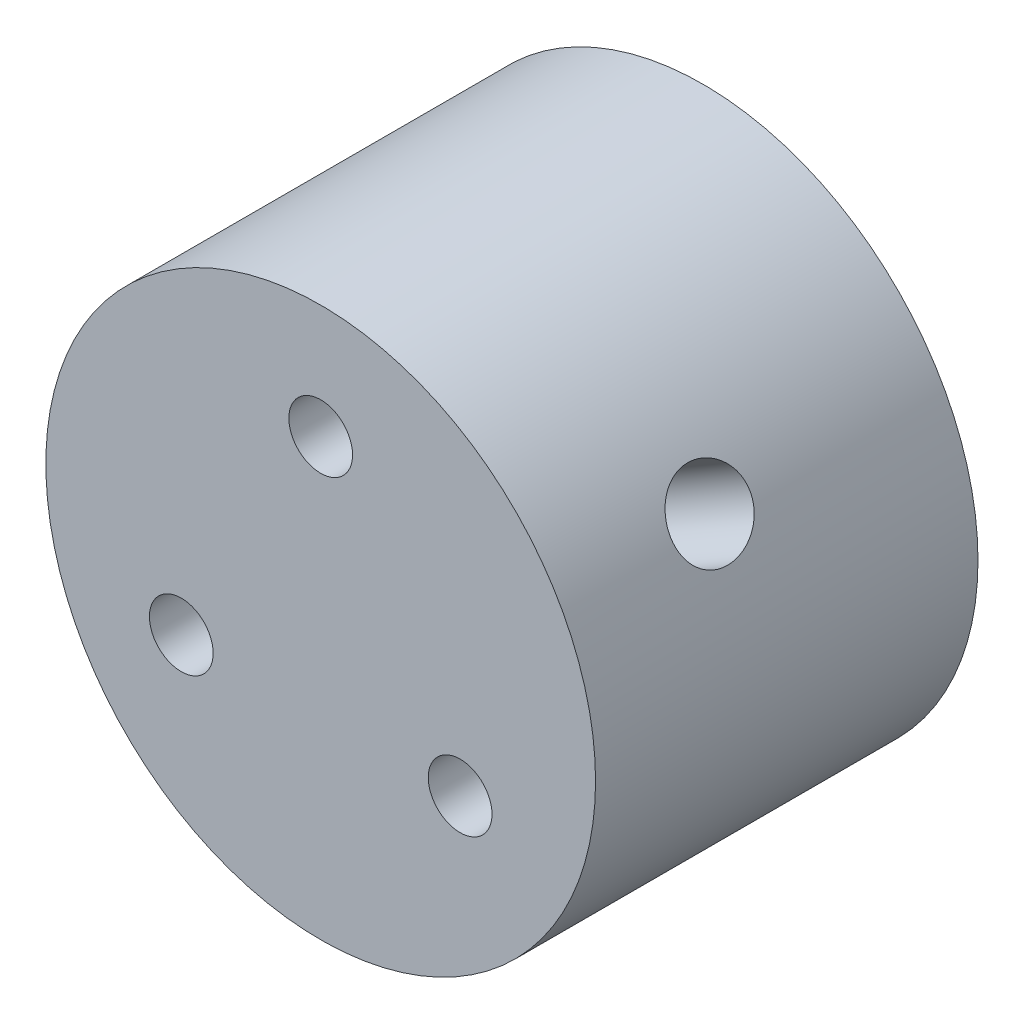
SolidWorks part; units mm, degrees
ref_plane "Přední rovina" through (0, 0, 0) normal (0, 0, 1) x (1, 0, 0)
ref_plane "Horní rovina" through (0, 0, 0) normal (0, 1, 0) x (1, 0, 0)
ref_plane "Pravá rovina" through (0, 0, 0) normal (1, 0, 0) x (0, 0, -1)
sketch "Skica1" plane through (0, 0, 0) normal (0, 0, 1) x (1, 0, 0)
  circle A0 centre (0, 0) radius 34.5
  dimension "D1" = 69
extrude "Přidat vysunutím1" add sketch "Skica1" along normal blind 48
sketch "Skica2" plane through (0, 0, 48) normal (0, 0, 1) x (1, 0, 0)
  line L1 (0, 20.2073) -> (-17.5, -10.1036) construction
  line L2 (-17.5, -10.1036) -> (17.5, -10.1036) construction
  line L3 (17.5, -10.1036) -> (0, 20.2073) construction
  circle A0 centre (0, 0) radius 10.1036 construction
  circle A1 centre (0, 20.2073) radius 4
  circle A2 centre (17.5, -10.1036) radius 4
  circle A3 centre (-17.5, -10.1036) radius 4
  dimension "D2" = 8
  dimension "D1" = 35
extrude "Odebrat vysunutím1" cut sketch "Skica2" against normal blind 40
sketch "Skica3" plane through (0, 0, 0) normal (0, 1, 0) x (1, 0, 0)
  line L0 (0, 0) -> (0, -42.7972) construction
  line L1 (-34.5, -48) -> (34.5, -48) construction
  circle A0 centre (0, -29) radius 5
  dimension "D1" = 10
  dimension "D2" = 19
extrude "Odebrat vysunutím2" cut sketch "Skica3" against normal through all
pattern_circular "Kruhové pole1" count 3 over 360 about axis through (0, 0, 48) along (0, 0, -1) of "Odebrat vysunutím2"
